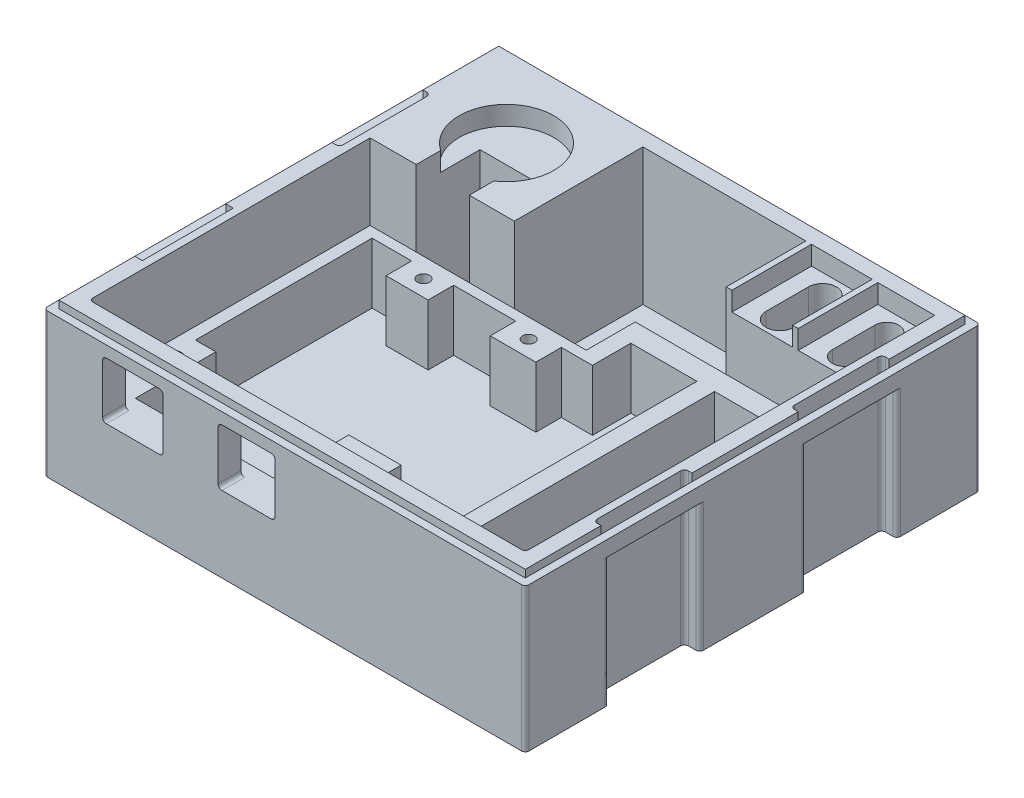
SolidWorks part; units mm, degrees
ref_plane "Alzado" through (0, 0, 0) normal (0, 0, 1) x (1, 0, 0)
ref_plane "Planta" through (0, 0, 0) normal (0, 1, 0) x (1, 0, 0)
ref_plane "Vista lateral" through (0, 0, 0) normal (1, 0, 0) x (0, 0, -1)
sketch "Croquis1" plane through (0, 0, 0) normal (0, 1, 0) x (1, 0, 0)
  line L1 (-51.0345, 37.8507) -> (75.9655, 37.8507)
  line L2 (-51.0345, 37.8507) -> (-51.0345, -82.1493)
  line L3 (-51.0345, -82.1493) -> (75.9655, -82.1493)
  line L4 (75.9655, 37.8507) -> (75.9655, -82.1493)
  dimension "D1" = 127
  dimension "D2" = 120
extrude "Saliente-Extruir1" add sketch "Croquis1" along normal blind 40 contours L2 L1 L4 L3
sketch "Croquis2" plane through (0, 40, 0) normal (0, 1, 0) x (1, 0, 0)
  line L0 (-51.0345, 37.8507) -> (-51.0345, -82.1493) construction
  line L1 (-45.0345, 31.8507) -> (69.9655, 31.8507)
  line L2 (-45.0345, 31.8507) -> (-45.0345, -76.1493)
  line L3 (-45.0345, -76.1493) -> (69.9655, -76.1493)
  line L4 (69.9655, 31.8507) -> (69.9655, -76.1493)
  line L5 (-51.0345, -82.1493) -> (75.9655, -82.1493) construction
  line L7 (-51.0345, 37.8507) -> (75.9655, 37.8507) construction
  dimension "D1" = 115
  dimension "D2" = 6
  dimension "D3" = 6
  dimension "D4" = 6
extrude "Cortar-Extruir1" cut sketch "Croquis2" against normal blind 20
ref_plane "Plano9" through (0, 0, 22.1493) normal (0, 0, -1) x (-1, 0, 0)
ref_plane "Plano10" through (12.4655, 0, 0) normal (1, 0, 0) x (0, 0, -1)
sketch "Croquis15" plane through (0, 0, 76.1493) normal (0, 0, -1) x (-1, 0, 0)
  line L0 (45.0345, 20) -> (-69.9655, 20) construction
  line L1 (35.5345, 20) -> (19.5345, 20)
  line L2 (35.5345, 20) -> (35.5345, 35)
  line L3 (35.5345, 35) -> (19.5345, 35)
  line L4 (19.5345, 20) -> (19.5345, 35)
  line L5 (45.0345, 20) -> (45.0345, 40) construction
  dimension "D1" = 16
  dimension "D2" = 15
  dimension "D3" = 9.5
sketch "Croquis16" plane through (0, 20, 0) normal (0, 1, 0) x (1, 0, 0)
  line L0 (-45.0345, -76.1493) -> (69.9655, -76.1493) construction
  line L1 (-43.5345, -73.1493) -> (9.4655, -73.1493)
  line L2 (-43.5345, -73.1493) -> (-43.5345, -7.206)
  line L4 (9.4655, -73.1493) -> (9.4655, -7.1493)
  line L5 (69.9655, -76.1493) -> (69.9655, 31.8507) construction
  line L10 (13.9655, -73.1493) -> (68.9655, -73.1493)
  line L11 (13.9655, -73.1493) -> (13.9655, 8.8507)
  line L12 (13.9655, 8.8507) -> (68.9655, 8.8507)
  line L13 (68.9655, -73.1493) -> (68.9655, 8.8507)
  line L14 (-43.5345, -7.206) -> (-29.745, -7.206)
  line L15 (-29.745, -7.206) -> (-27.6114, -5.0723)
  line L16 (-27.6114, -5.0723) -> (4.3886, -5.0723)
  line L18 (6.4655, -7.1493) -> (9.4655, -7.1493)
  line L19 (4.3886, -5.0723) -> (6.4655, -7.1493)
  line L20 (-45.0345, -76.1493) -> (69.9655, -76.1493) construction
  line L21 (-29.745, -7.206) -> (6.4655, -7.1493) construction
  line L22 (-43.5345, -59.1493) -> (9.4655, -59.1493) construction
  line L23 (-43.5345, -7.206) -> (9.4655, -73.1493) construction
  line L24 (-43.5345, -73.1493) -> (9.4655, -7.1493) construction
  point P13 (-17.0345, -73.1493)
  dimension "D1" = 66
  dimension "D2" = 53
  dimension "D3" = 3
  dimension "D4" = 14
  dimension "D5" = 32
  dimension "D6" = 3
  dimension "D7" = 45
  dimension "D8" = 82
  dimension "D9" = 55
  dimension "D10" = 1
  dimension "D11" = 3
extrude "Cortar-Extruir3" cut sketch "Croquis15" against normal blind 14
fillet "Redondeo4" radius 1 4 edges at (-35.5345, 35, 79.1493) (-19.5345, 35, 79.1493) (-19.5345, 20, 79.1493) (-35.5345, 20, 79.1493)
fillet "Redondeo5" radius 1 2 edges at (-45.0345, 30, 76.1493) (69.9655, 30, 76.1493)
sketch "Croquis17" plane through (0, 20, 0) normal (0, 1, 0) x (1, 0, 0)
  line L0 (-43.5345, -73.1493) -> (-43.5345, -7.206) construction
  line L1 (-43.5345, -73.1493) -> (9.4655, -73.1493) construction
  line L4 (-43.5345, -59.1493) -> (9.4655, -59.1493) construction
  line L5 (9.4655, -73.1493) -> (9.4655, -7.1493) construction
  line L6 (-29.745, -7.206) -> (6.4655, -7.1493) construction
  circle A0 centre (-25.815, -7.1998) radius 1.6
  circle A1 centre (1.8655, -7.1565) radius 1.6
  circle A2 centre (-41.0345, -57.5493) radius 1.6
  circle A3 centre (6.9655, -59.1493) radius 1.6
  point P0 (-41.0345, -57.5493)
  point P5 (6.9655, -59.1493)
  point P10 (-25.815, -7.1998)
  point P11 (1.8655, -7.1565)
  dimension "D6" = 3.2
  dimension "D7" = 3.2
  dimension "D8" = 3.2
  dimension "D9" = 3.2
  dimension "D1" = 2.5
  dimension "D2" = 15.6
  dimension "D3" = 2.5
  dimension "D4" = 3.93
  dimension "D5" = 4.6
hole_wizard "Taladro de margen para M31" positions "Croquis17" profile "Croquis18" hole size "M3" standard "JIS"
sketch "Croquis18" plane through (-41.0345, 20, 57.5493) normal (1, 0, 0) x (0, 0, 1)
  line L0 (0, 0) -> (0, 15.9614)
  line L1 (0, 15.9614) -> (1.6, 15)
  line L2 (1.6, 15) -> (1.6, 0)
  line L5 (1.6, 0) -> (0, 0)
  line L10 (0, 15.9614) -> (-1.6, 15) construction
  line L11 (0, -6.35) -> (0, 107.95) construction
  dimension "Diámetro de taladro" = 3.2
  dimension "Profundidad de taladro" = 15
  dimension "Ángulo de perforador" = 118
sketch "Croquis21" plane through (0, 20, 0) normal (0, 1, 0) x (1, 0, 0)
  line L0 (-45.0345, -2.0723) -> (11.9655, -2.0723)
  line L1 (-45.0345, 31.8507) -> (-45.0345, -75.1493) construction
  line L2 (11.9655, -2.0723) -> (11.9655, 10.8507)
  line L3 (11.9655, 10.8507) -> (69.9655, 10.8507)
  line L4 (69.9655, -75.1493) -> (69.9655, 31.8507) construction
  line L5 (-27.6114, -5.0723) -> (4.3886, -5.0723) construction
  line L6 (13.9655, 8.8507) -> (68.9655, 8.8507) construction
  line L7 (13.9655, -73.1493) -> (13.9655, 8.8507) construction
  line L8 (-45.0345, -2.0723) -> (-45.0345, 31.8507)
  line L9 (69.9655, 31.8507) -> (-45.0345, 31.8507) construction
  line L10 (-45.0345, 31.8507) -> (69.9655, 31.8507)
  line L11 (69.9655, 31.8507) -> (69.9655, 10.8507)
  dimension "D1" = 3
  dimension "D2" = 2
  dimension "D3" = 2
extrude "Saliente-Extruir4" add sketch "Croquis21" along normal blind 15
sketch "Croquis22" plane through (0, 35, 0) normal (0, 1, 0) x (1, 0, 0)
  line L0 (11.9655, 10.8507) -> (69.9655, 10.8507) construction
  line L1 (53.4655, 10.8507) -> (54.9655, 10.8507)
  line L2 (53.4655, 10.8507) -> (53.4655, 31.8507)
  line L3 (53.4655, 31.8507) -> (54.9655, 31.8507)
  line L4 (54.9655, 10.8507) -> (54.9655, 31.8507)
  line L5 (69.9655, 31.8507) -> (-45.0345, 31.8507) construction
  line L6 (69.9655, 10.8507) -> (69.9655, 31.8507) construction
  line L8 (35.9655, 31.8507) -> (37.4655, 31.8507)
  line L9 (35.9655, 31.8507) -> (35.9655, 10.8507)
  line L10 (35.9655, 10.8507) -> (37.4655, 10.8507)
  line L11 (37.4655, 31.8507) -> (37.4655, 10.8507)
  dimension "D1" = 1.5
  dimension "D2" = 15
  dimension "D3" = 1.5
  dimension "D4" = 16
extrude "Saliente-Extruir5" add sketch "Croquis22" along normal blind 5
sketch "Croquis24" plane through (0, 35, 0) normal (0, 1, 0) x (1, 0, 0)
  line L0 (-45.0345, -2.0723) -> (11.9655, -2.0723) construction
  line L1 (-45.0345, 31.8507) -> (-7.0014, 31.8507)
  line L2 (-45.0345, 31.8507) -> (-45.0345, -2.0723)
  line L3 (-45.0345, -2.0723) -> (-7.0014, -2.0723)
  line L4 (-7.0014, 31.8507) -> (-7.0014, -2.0723)
  line L5 (-45.0345, 31.8507) -> (-45.0345, -75.1493) construction
  line L6 (35.9655, 31.8507) -> (-45.0345, 31.8507) construction
  circle A1 centre (-25.8715, 14.7428) radius 12.5
  dimension "D1" = 25
  dimension "D2" = 0
  dimension "D3" = 0
extrude "Saliente-Extruir8" add sketch "Croquis24" along normal blind 5
sketch "Croquis25" plane through (0, 40, 0) normal (0, 1, 0) x (1, 0, 0)
  line L0 (-45.0345, -2.0723) -> (11.9655, -2.0723) construction
  line L1 (-32.8715, -2.0723) -> (-18.8715, -2.0723)
  line L2 (-32.8715, -2.0723) -> (-32.8715, 4.3866)
  line L3 (-32.8715, 4.3866) -> (-18.8715, 4.3866)
  line L4 (-18.8715, -2.0723) -> (-18.8715, 4.3866)
  circle A0 centre (-25.8715, 14.7428) radius 12.5 construction
  circle A1 centre (-25.8715, 14.7428) radius 12.5 construction
  dimension "D1" = 7
  dimension "D2" = 7
extrude "Cortar-Extruir4" cut sketch "Croquis25" against normal blind 5
sketch "Croquis27" plane through (0, 35, 0) normal (0, 1, 0) x (1, 0, 0)
  line L0 (-32.8715, -2.0723) -> (-18.8715, -2.0723) construction
  line L1 (-32.8715, 14.7428) -> (-18.8715, 14.7428)
  line L2 (-32.8715, 14.7428) -> (-32.8715, -2.0723)
  line L3 (-32.8715, -2.0723) -> (-18.8715, -2.0723)
  line L4 (-18.8715, 14.7428) -> (-18.8715, -2.0723)
  line L5 (-32.8715, 4.3866) -> (-32.8715, -2.0723) construction
  line L6 (-18.8715, -2.0723) -> (-18.8715, 4.3866) construction
  arc A0 (-18.8715, 4.3866) -> (-32.8715, 4.3866) centre (-25.8715, 14.7428) ccw construction
  point P9 (-25.8715, 14.7428)
  dimension "D1" = 0
  dimension "D2" = 0
  dimension "D3" = 0
extrude "Cortar-Extruir5" cut sketch "Croquis27" against normal blind 84.1
sketch "Croquis28" plane through (0, 0, 82.1493) normal (0, 0, 1) x (1, 0, 0)
  line L0 (-34.5345, 35) -> (-20.5345, 35) construction
  line L1 (-5.0345, 35) -> (9.9655, 35)
  line L2 (-5.0345, 35) -> (-5.0345, 20)
  line L3 (-5.0345, 20) -> (9.9655, 20)
  line L4 (9.9655, 35) -> (9.9655, 20)
  line L6 (-19.5345, 34) -> (-19.5345, 21) construction
  dimension "D1" = 0
  dimension "D2" = 15
  dimension "D3" = 15
  dimension "D4" = 14.5
extrude "Cortar-Extruir6" cut sketch "Croquis28" against normal blind 10
fillet "Redondeo7" radius 1 4 edges at (9.9655, 20, 79.1493) (-5.0345, 20, 79.1493) (9.9655, 35, 79.1493) (-5.0345, 35, 79.1493)
ref_plane "Plano11" through (42.4655, 0, 0) normal (1, 0, 0) x (0, 0, -1)
sketch "Croquis32" plane through (0, 40, 0) normal (0, 1, 0) x (1, 0, 0)
  line L9 (-49.0345, 35.8507) -> (73.9655, 35.8507)
  line L10 (73.9655, 35.8507) -> (73.9655, -80.1493)
  line L11 (73.9655, -80.1493) -> (-49.0345, -80.1493)
  line L12 (-49.0345, -80.1493) -> (-49.0345, 35.8507)
  line L13 (-51.0345, 37.8507) -> (-51.0345, -82.1493) construction
  line L14 (-51.0345, 37.8507) -> (75.9655, 37.8507) construction
  line L15 (75.9655, 37.8507) -> (75.9655, -82.1493) construction
  line L16 (-51.0345, -82.1493) -> (75.9655, -82.1493) construction
  dimension "D1" = 2
  dimension "D2" = 2
  dimension "D3" = 2
  dimension "D4" = 2
extrude "Cortar-Extruir7" cut sketch "Croquis32" against normal blind 2 flip side to cut
sketch "Croquis33" plane through (0, 0, 0) normal (0, -1, 0) x (-1, 0, 0)
  line L0 (-75.9655, 37.8507) -> (-75.9655, -82.1493) construction
  line L1 (51.0345, -82.1493) -> (-75.9655, -82.1493) construction
  line L2 (51.0345, 37.8507) -> (-75.9655, 37.8507) construction
  point P0 (-75.9655, -60.1493)
  point P1 (-75.9655, -36.1493)
  point P4 (-75.9655, -8.1493)
  point P5 (-75.9655, 15.8507)
  dimension "D1" = 22
  dimension "D2" = 22
  dimension "D3" = 24
  dimension "D4" = 24
sketch "Croquis34" plane through (75.9655, 0, 0) normal (1, 0, 0) x (0, 0, -1)
  line L0 (37.8507, 38) -> (-82.1493, 38) construction
  line L1 (-60.1493, 0) -> (-36.1493, 0)
  line L2 (-60.1493, 0) -> (-60.1493, 34)
  line L3 (-60.1493, 34) -> (-36.1493, 34)
  line L4 (-36.1493, 0) -> (-36.1493, 34)
  line L6 (-8.1493, 0) -> (15.8507, 0)
  line L7 (-8.1493, 0) -> (-8.1493, 34)
  line L8 (-8.1493, 34) -> (15.8507, 34)
  line L9 (15.8507, 0) -> (15.8507, 34)
  dimension "D1" = 0
  dimension "D2" = 4
  dimension "D3" = 0
  dimension "D4" = 4
extrude "Cortar-Extruir8" cut sketch "Croquis34" against normal blind 4
sketch "Croquis35" plane through (0, 34, 0) normal (0, -1, 0) x (1, 0, 0)
  line L0 (71.9655, 36.1493) -> (75.9655, 36.1493) construction
  line L1 (71.9655, 60.1493) -> (73.9655, 60.1493)
  line L2 (71.9655, 60.1493) -> (71.9655, 36.1493)
  line L3 (71.9655, 36.1493) -> (73.9655, 36.1493)
  line L4 (73.9655, 60.1493) -> (73.9655, 36.1493)
  line L6 (71.9655, 8.1493) -> (73.9655, 8.1493)
  line L7 (71.9655, 8.1493) -> (71.9655, -15.8507)
  line L8 (71.9655, -15.8507) -> (73.9655, -15.8507)
  line L9 (73.9655, 8.1493) -> (73.9655, -15.8507)
  dimension "D1" = 24
  dimension "D2" = 2
  dimension "D3" = 24
  dimension "D4" = 2
extrude "Cortar-Extruir9" cut sketch "Croquis35" against normal blind 20
fillet "Redondeo13" radius 1 8 edges at (75.9655, 17, -15.8507) (71.9655, 20, -15.8507) (71.9655, 20, 8.1493) (75.9655, 17, 8.1493) (75.9655, 17, 36.1493) (71.9655, 20, 36.1493) (71.9655, 20, 60.1493) (75.9655, 17, 60.1493)
mirror "Simetría2" about plane through (12.4655, 0, 0) normal (1, 0, 0) of "Cortar-Extruir8", "Cortar-Extruir9"
fillet "Redondeo19" radius 1 6 edges at (-51.0345, 17, 60.1493) (-51.0345, 17, 36.1493) (-51.0345, 17, 8.1493) (-51.0345, 17, -15.8507) (-47.0345, 20, 8.1493) (-47.0345, 20, -15.8507)
fillet "Redondeo14" radius 1 4 edges at (75.9655, 19, -37.8507) (75.9655, 19, 82.1493) (-51.0345, 19, -37.8507) (-51.0345, 19, 82.1493)
sketch "Croquis36" plane through (0, 0, 0) normal (0, -1, 0) x (-1, 0, 0)
  line L0 (-12.4655, -82.1493) -> (-12.4655, 37.8507) construction
  line L1 (50.0345, -82.1493) -> (-74.9655, -82.1493) construction
  line L2 (50.0345, 37.8507) -> (-74.9655, 37.8507) construction
  circle A0 centre (-12.4655, -58.1493) radius 2.5
  circle A1 centre (-12.4655, 13.8507) radius 2.5
  circle A2 centre (-12.4655, -10.1493) radius 2.5
  circle A3 centre (-12.4655, -34.1493) radius 2.5
  point P10 (-12.4655, -10.1493)
  point P11 (-12.4655, -34.1493)
  dimension "D1" = 24
  dimension "D2" = 24
  dimension "D3" = 5
  dimension "D4" = 5
  dimension "D8" = 5
  dimension "D9" = 5
  dimension "D5" = 120
  dimension "D6" = 24
  dimension "D7" = 24
extrude "Cortar-Extruir10" cut sketch "Croquis36" against normal blind 1
sketch "Croquis44" plane through (0, 35, 0) normal (0, 1, 0) x (1, 0, 0)
  line L0 (45.4655, 31.8507) -> (45.4655, 10.8507) construction
  line L1 (53.4655, 31.8507) -> (37.4655, 31.8507) construction
  line L2 (37.4655, 10.8507) -> (53.4655, 10.8507) construction
  line L3 (62.4655, 31.8507) -> (62.4655, 10.8507) construction
  line L4 (69.9655, 31.8507) -> (54.9655, 31.8507) construction
  line L5 (54.9655, 10.8507) -> (69.9655, 10.8507) construction
  line L6 (45.4655, 26.7283) -> (45.4655, 15.5184) construction
  line L7 (49.1333, 26.7283) -> (49.1333, 15.5184)
  line L8 (41.7978, 26.7283) -> (41.7978, 15.5184)
  line L9 (62.4655, 26.7283) -> (62.4655, 15.5184) construction
  line L10 (65.6333, 26.7283) -> (65.6333, 15.5184)
  line L11 (59.2978, 26.7283) -> (59.2978, 15.5184)
  arc A0 (49.1333, 26.7283) -> (41.7978, 26.7283) centre (45.4655, 26.7283) ccw
  arc A1 (41.7978, 15.5184) -> (49.1333, 15.5184) centre (45.4655, 15.5184) ccw
  arc A2 (65.6333, 26.7283) -> (59.2978, 26.7283) centre (62.4655, 26.7283) ccw
  arc A3 (59.2978, 15.5184) -> (65.6333, 15.5184) centre (62.4655, 15.5184) ccw
  point P14 (45.4655, 21.1233)
  point P21 (62.4655, 21.1233)
  point P26 (0, 0)
  dimension "D1" = 0
extrude "Cortar-Extruir14" cut sketch "Croquis44" against normal blind 39
sketch "Croquis45" plane through (0, 20, 0) normal (0, 1, 0) x (1, 0, 0)
  line L0 (-31.4581, -4.7111) -> (-31.4581, -11.4483)
  line L1 (-31.4581, -11.4483) -> (-20.3615, -11.4483)
  line L2 (-20.3615, -11.4483) -> (-20.3615, -4.7111)
  line L3 (-20.3615, -4.7111) -> (-3.9808, -4.7111)
  line L4 (-3.9808, -4.7111) -> (-3.9808, -11.4483)
  line L5 (-3.9808, -11.4483) -> (8.0405, -11.4483)
  line L6 (8.0405, -11.4483) -> (8.0405, -4.7111)
  line L7 (8.0405, -4.7111) -> (16.2309, -4.7111)
  line L8 (16.2309, -4.7111) -> (16.2309, 5.4273)
  line L9 (16.2309, 5.4273) -> (33.6684, 5.4273)
  line L10 (33.6684, 5.4273) -> (33.6684, -72.517)
  line L11 (33.6684, -72.517) -> (13.808, -72.517)
  line L12 (13.808, -72.517) -> (13.808, -52.7288)
  line L13 (13.808, -52.7288) -> (0, -52.7288)
  line L14 (0, -52.7288) -> (0, -72.517)
  line L15 (0, -72.517) -> (-36.5143, -72.517)
  line L16 (-36.5143, -72.517) -> (-36.5143, -51.2873)
  line L17 (-36.5143, -51.2873) -> (-41.8872, -51.2873)
  line L18 (-41.8872, -51.2873) -> (-41.8872, -4.7111)
  line L19 (-41.8872, -4.7111) -> (-31.4581, -4.7111)
  line L20 (38.3139, 5.4273) -> (63.8682, 5.4273)
  line L21 (63.8682, 5.4273) -> (63.8682, -72.517)
  line L22 (63.8682, -72.517) -> (38.3139, -72.517)
  line L23 (38.3139, -72.517) -> (38.3139, 5.4273)
extrude "Cortar-Extruir15" cut sketch "Croquis45" against normal blind 16
sketch "Croquis46" plane through (0, 35, 0) normal (0, 1, 0) x (1, 0, 0)
  line L0 (-7.0014, 31.8507) -> (35.9655, 31.8507)
  line L1 (35.9655, 31.8507) -> (35.9655, 10.8507)
  line L2 (35.9655, 10.8507) -> (11.9655, 10.8507)
  line L3 (11.9655, 10.8507) -> (11.9655, -2.0723)
  line L4 (11.9655, -2.0723) -> (-7.0014, -2.0723)
  line L5 (-7.0014, -2.0723) -> (-7.0014, 31.8507)
extrude "Cortar-Extruir16" cut sketch "Croquis46" against normal blind 31
